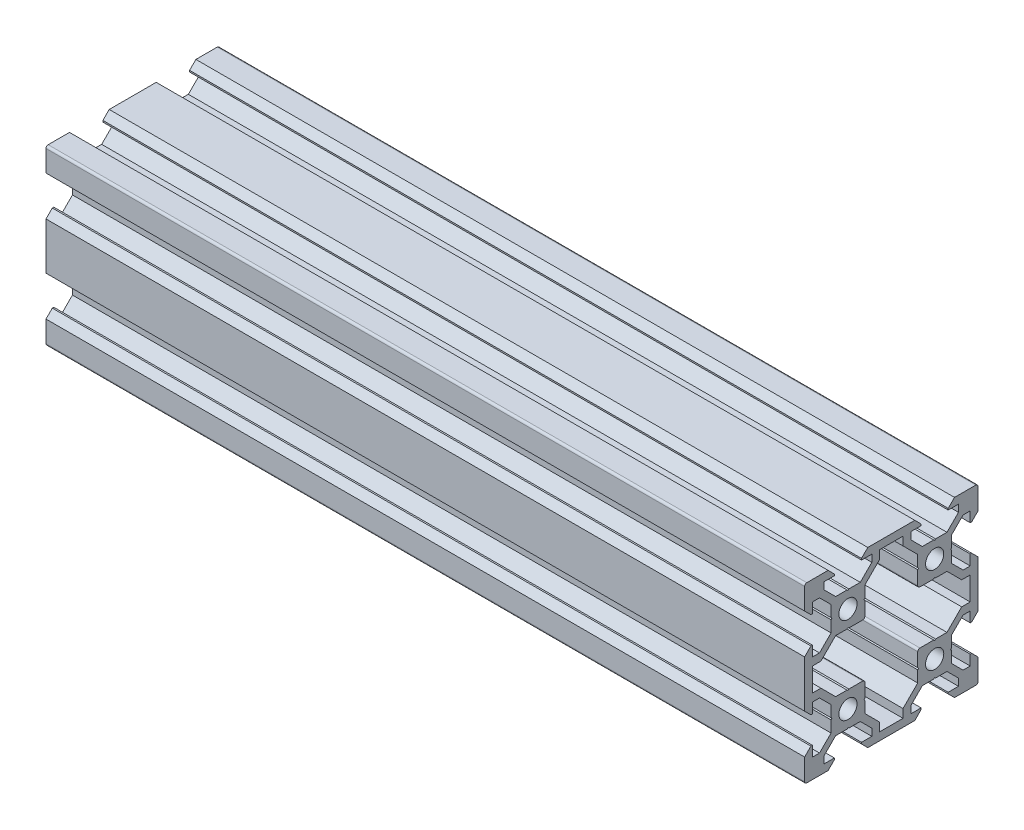
SolidWorks part; units mm, degrees
material "6061-T6 (SS)"
ref_plane "Top" through (0, 0, 0) normal (0, 0, 1) x (1, 0, 0)
ref_plane "Front" through (0, 0, 0) normal (0, 1, 0) x (1, 0, 0)
ref_plane "Right" through (0, 0, 0) normal (1, 0, 0) x (0, 0, -1)
sketch "Profile Sketch" plane through (0, 0, 0) normal (1, 0, 0) x (0, 0, -1)
  line L0 (0, 10) -> (-5.42, 10)
  line L1 (-4.5, 8.2) -> (-4.5, 6.56)
  line L2 (-4.5, 6.56) -> (-7.16, 3.9)
  line L3 (-7.16, 3.9) -> (-9.79, 3.9)
  line L4 (-9.79, 3.9) -> (-10, 3.69)
  line L5 (2.7, 8.2) -> (-2.7, 8.2)
  line L6 (-2.7, 8.2) -> (-2.7, 6.2387)
  line L7 (-2.7, 6.2387) -> (-6.1, 2.8387)
  line L8 (-6.1, 2.8387) -> (-6.1, 0.21)
  line L9 (-6.875, 8.545) -> (-6.875, 8.2)
  line L10 (-6.875, 8.2) -> (-4.5, 8.2)
  line L11 (-6.875, 8.545) -> (-5.42, 10)
  line L12 (0, -10) -> (0, 10) construction
  line L13 (-20, 0) -> (20, 0) construction
  line L14 (-10, -10) -> (-10, 10) construction
  line L21 (-6.6, -3.9) -> (-9.79, -3.9)
  line L25 (-10, 0) -> (-20, 10) construction
  line L26 (-18.545, 3.125) -> (-18.2, 3.125)
  line L31 (-16.2383, -7.3) -> (-12.84, -3.9)
  line L32 (-12.84, -3.9) -> (-10.21, -3.9)
  line L33 (-20, 4.58) -> (-20, 9.5)
  line L34 (-13.9, 2.8387) -> (-13.9, 0.21)
  line L35 (-16.56, 5.5) -> (-13.9, 2.8387)
  line L36 (-12.84, 3.9) -> (-10.21, 3.9)
  line L37 (-15.5, 6.56) -> (-12.84, 3.9)
  line L38 (-15.5, 8.2) -> (-15.5, 6.56)
  line L39 (-13.125, 8.545) -> (-14.58, 10)
  line L40 (-13.125, 8.2) -> (-15.5, 8.2)
  line L41 (-13.125, 8.545) -> (-13.125, 8.2)
  line L42 (-18.2, 3.125) -> (-18.2, 5.5)
  line L43 (-18.545, 3.125) -> (-20, 4.58)
  line L44 (-18.2, 5.5) -> (-16.56, 5.5)
  line L45 (-14.58, 10) -> (-19.5, 10)
  line L46 (-16.56, -5.5) -> (-13.9, -2.8387)
  line L48 (-18.2, -5.5) -> (-16.56, -5.5)
  line L49 (-18.545, -3.125) -> (-20, -4.58)
  line L50 (-18.2, -3.125) -> (-18.2, -5.5)
  line L51 (-20, -4.58) -> (-20, -15.42)
  line L52 (-18.545, -3.125) -> (-18.2, -3.125)
  line L53 (9.79, -3.9) -> (10, -3.69)
  line L99 (-10, 3.69) -> (-10.21, 3.9)
  line L100 (-10, -3.69) -> (-10.21, -3.9)
  line L101 (-9.79, -3.9) -> (-10, -3.69)
  line L102 (-13.9, -0.21) -> (-13.69, 0)
  line L103 (-13.69, 0) -> (-13.9, 0.21)
  line L104 (-13.9, -0.21) -> (-13.9, -2.8387)
  line L105 (-6.1, -0.21) -> (-6.31, 0)
  line L106 (-6.31, 0) -> (-6.1, -0.21)
  line L107 (-6.1, -0.21) -> (-6.1, -3.4)
  line L117 (-16.2383, -7.3) -> (-18.2, -7.3)
  line L118 (20, -10) -> (20, 10) construction
  line L119 (20, -10) -> (-20, -10) construction
  line L120 (-20, -10) -> (-20, 10) construction
  line L121 (20, 10) -> (-20, 10) construction
  line L122 (6.6, -3.9) -> (9.79, -3.9)
  line L123 (10, -3.69) -> (10.21, -3.9)
  line L124 (-18.2, -7.3) -> (-18.2, -12.7)
  line L125 (12.84, -3.9) -> (10.21, -3.9)
  line L126 (-6.31, 0) -> (-6.1, 0.21)
  line L127 (16.2383, -7.3) -> (12.84, -3.9)
  line L128 (20, -4.58) -> (20, -15.42)
  line L129 (18.2, -7.3) -> (18.2, -12.7)
  line L130 (16.2383, -7.3) -> (18.2, -7.3)
  line L131 (18.545, -3.125) -> (18.2, -3.125)
  line L132 (18.2, -3.125) -> (18.2, -5.5)
  line L133 (18.545, -3.125) -> (20, -4.58)
  line L134 (18.2, -5.5) -> (16.56, -5.5)
  line L135 (16.56, -5.5) -> (13.9, -2.8387)
  line L136 (13.9, -0.21) -> (13.9, -2.8387)
  line L137 (13.69, 0) -> (13.9, 0.21)
  line L138 (13.9, -0.21) -> (13.69, 0)
  line L139 (13.9, 2.8387) -> (13.9, 0.21)
  line L140 (18.2, 5.5) -> (16.56, 5.5)
  line L141 (18.545, 3.125) -> (20, 4.58)
  line L142 (18.2, 3.125) -> (18.2, 5.5)
  line L143 (16.56, 5.5) -> (13.9, 2.8387)
  line L144 (18.545, 3.125) -> (18.2, 3.125)
  line L145 (20, 4.58) -> (20, 9.5)
  line L146 (14.58, 10) -> (19.5, 10)
  line L147 (13.125, 8.545) -> (13.125, 8.2)
  line L148 (13.125, 8.2) -> (15.5, 8.2)
  line L149 (13.125, 8.545) -> (14.58, 10)
  line L150 (15.5, 8.2) -> (15.5, 6.56)
  line L151 (15.5, 6.56) -> (12.84, 3.9)
  line L152 (12.84, 3.9) -> (10.21, 3.9)
  line L153 (10, 3.69) -> (10.21, 3.9)
  line L154 (9.79, 3.9) -> (10, 3.69)
  line L155 (6.1, -0.21) -> (6.1, -3.4)
  line L156 (6.1, -0.21) -> (6.31, 0)
  line L157 (6.31, 0) -> (6.1, 0.21)
  line L158 (6.1, 2.8387) -> (6.1, 0.21)
  line L159 (7.16, 3.9) -> (9.79, 3.9)
  line L160 (2.7, 6.2387) -> (6.1, 2.8387)
  line L161 (4.5, 6.56) -> (7.16, 3.9)
  line L162 (6.875, 8.545) -> (6.875, 8.2)
  line L163 (6.875, 8.2) -> (4.5, 8.2)
  line L164 (4.5, 8.2) -> (4.5, 6.56)
  line L165 (2.7, 8.2) -> (2.7, 6.2387)
  line L166 (6.875, 8.545) -> (5.42, 10)
  line L167 (0, 10) -> (5.42, 10)
  line L168 (-20, -24.58) -> (-20, -29.5)
  line L169 (-14.58, -30) -> (-19.5, -30)
  line L170 (-7.16, -23.9) -> (-9.79, -23.9)
  line L171 (-10, -23.69) -> (-10.21, -23.9)
  line L172 (-9.79, -23.9) -> (-10, -23.69)
  line L173 (-12.84, -23.9) -> (-10.21, -23.9)
  line L174 (-13.125, -28.545) -> (-13.125, -28.2)
  line L175 (-13.125, -28.2) -> (-15.5, -28.2)
  line L176 (-13.125, -28.545) -> (-14.58, -30)
  line L177 (-15.5, -28.2) -> (-15.5, -26.56)
  line L178 (-15.5, -26.56) -> (-12.84, -23.9)
  line L179 (-18.2, -25.5) -> (-16.56, -25.5)
  line L180 (-18.545, -23.125) -> (-20, -24.58)
  line L181 (-18.2, -23.125) -> (-18.2, -25.5)
  line L182 (-16.56, -25.5) -> (-13.9, -22.8387)
  line L183 (-18.545, -23.125) -> (-18.2, -23.125)
  line L184 (-13.9, -19.79) -> (-13.9, -17.1613)
  line L185 (-13.69, -20) -> (-13.9, -20.21)
  line L186 (-13.9, -19.79) -> (-13.69, -20)
  line L187 (-13.9, -22.8387) -> (-13.9, -20.21)
  line L188 (-16.2383, -12.7) -> (-18.2, -12.7)
  line L189 (-18.545, -16.875) -> (-18.2, -16.875)
  line L190 (-18.2, -16.875) -> (-18.2, -14.5)
  line L191 (-18.545, -16.875) -> (-20, -15.42)
  line L192 (-18.2, -14.5) -> (-16.56, -14.5)
  line L193 (-16.56, -14.5) -> (-13.9, -17.1613)
  line L194 (-16.2383, -12.7) -> (-12.84, -16.1)
  line L195 (-9.79, -16.1) -> (-10, -16.31)
  line L196 (-10, -16.31) -> (-10.21, -16.1)
  line L197 (-12.84, -16.1) -> (-10.21, -16.1)
  line L198 (-6.6, -16.1) -> (-9.79, -16.1)
  line L199 (-6.1, -19.79) -> (-6.1, -16.6)
  line L200 (-6.1, -22.8387) -> (-6.1, -20.21)
  line L201 (-6.31, -20) -> (-6.1, -20.21)
  line L202 (-6.31, -20) -> (-6.1, -19.79)
  line L203 (-6.1, -19.79) -> (-6.31, -20)
  line L204 (-2.7, -26.2387) -> (-6.1, -22.8387)
  line L205 (-4.5, -26.56) -> (-7.16, -23.9)
  line L206 (-4.5, -28.2) -> (-4.5, -26.56)
  line L207 (-6.875, -28.2) -> (-4.5, -28.2)
  line L208 (-6.875, -28.545) -> (-6.875, -28.2)
  line L209 (-6.875, -28.545) -> (-5.42, -30)
  line L210 (0, -30) -> (-5.42, -30)
  line L211 (0, -30) -> (5.42, -30)
  line L212 (14.58, -30) -> (19.5, -30)
  line L213 (20, -24.58) -> (20, -29.5)
  line L214 (6.875, -28.545) -> (5.42, -30)
  line L215 (2.7, -28.2) -> (2.7, -26.2387)
  line L216 (4.5, -28.2) -> (4.5, -26.56)
  line L217 (6.875, -28.2) -> (4.5, -28.2)
  line L218 (6.875, -28.545) -> (6.875, -28.2)
  line L219 (4.5, -26.56) -> (7.16, -23.9)
  line L220 (2.7, -26.2387) -> (6.1, -22.8387)
  line L221 (7.16, -23.9) -> (9.79, -23.9)
  line L222 (6.1, -22.8387) -> (6.1, -20.21)
  line L223 (9.79, -23.9) -> (10, -23.69)
  line L224 (10, -23.69) -> (10.21, -23.9)
  line L225 (12.84, -23.9) -> (10.21, -23.9)
  line L226 (15.5, -26.56) -> (12.84, -23.9)
  line L227 (15.5, -28.2) -> (15.5, -26.56)
  line L228 (13.125, -28.545) -> (14.58, -30)
  line L229 (13.125, -28.2) -> (15.5, -28.2)
  line L230 (13.125, -28.545) -> (13.125, -28.2)
  line L231 (18.545, -23.125) -> (18.2, -23.125)
  line L232 (16.56, -25.5) -> (13.9, -22.8387)
  line L233 (18.2, -23.125) -> (18.2, -25.5)
  line L234 (18.545, -23.125) -> (20, -24.58)
  line L235 (18.2, -25.5) -> (16.56, -25.5)
  line L236 (13.9, -22.8387) -> (13.9, -20.21)
  line L237 (2.7, -28.2) -> (-2.7, -28.2)
  line L238 (6.31, -20) -> (6.1, -20.21)
  line L239 (6.1, -19.79) -> (6.31, -20)
  line L240 (13.9, -19.79) -> (13.69, -20)
  line L241 (13.69, -20) -> (13.9, -20.21)
  line L242 (6.1, -19.79) -> (6.1, -16.6)
  line L243 (13.9, -19.79) -> (13.9, -17.1613)
  line L244 (16.56, -14.5) -> (13.9, -17.1613)
  line L245 (18.2, -14.5) -> (16.56, -14.5)
  line L246 (18.545, -16.875) -> (20, -15.42)
  line L247 (18.2, -16.875) -> (18.2, -14.5)
  line L248 (18.545, -16.875) -> (18.2, -16.875)
  line L249 (16.2383, -12.7) -> (18.2, -12.7)
  line L250 (16.2383, -12.7) -> (12.84, -16.1)
  line L251 (12.84, -16.1) -> (10.21, -16.1)
  line L252 (10, -16.31) -> (10.21, -16.1)
  line L253 (6.6, -16.1) -> (9.79, -16.1)
  line L254 (9.79, -16.1) -> (10, -16.31)
  line L255 (-2.7, -26.2387) -> (-2.7, -28.2)
  circle A0 centre (-10, 0) radius 2.1
  arc A1 (-19.5, 10) -> (-20, 9.5) centre (-19.5, 9.5) ccw
  arc A2 (-6.6, -3.9) -> (-6.1, -3.4) centre (-6.6, -3.4) ccw
  arc A3 (6.6, -3.9) -> (6.1, -3.4) centre (6.6, -3.4) cw
  circle A4 centre (10, 0) radius 2.1
  arc A5 (19.5, 10) -> (20, 9.5) centre (19.5, 9.5) cw
  arc A6 (-19.5, -30) -> (-20, -29.5) centre (-19.5, -29.5) cw
  arc A7 (-6.6, -16.1) -> (-6.1, -16.6) centre (-6.6, -16.6) cw
  arc A8 (19.5, -30) -> (20, -29.5) centre (19.5, -29.5) ccw
  circle A9 centre (10, -20) radius 2.1
  arc A10 (6.6, -16.1) -> (6.1, -16.6) centre (6.6, -16.6) ccw
  circle A11 centre (-10, -20) radius 2.1
  point P35 (-2.4957, 0)
  point P119 (0, 18.9743)
  point P121 (0, 8.2)
  point P123 (2.4957, 0)
  point P131 (0, 0)
  point P143 (0, 0)
  point P164 (-18.2, -10)
  point P234 (18.2, -10)
  dimension "D4" = 5.42
  dimension "D5" = 40
  dimension "D6" = 4.2
  dimension "D16" = 0.5
  dimension "D17" = 0.5
  dimension "D2" = 45
  dimension "D3" = 20
  dimension "D7" = 1.5
  dimension "D9" = 10
  dimension "D10" = 3.9
  dimension "D11" = 3.9
  dimension "D13" = 3.125
  dimension "D14" = 5.5
  dimension "D15" = 1.64
extrude "Profile Extrude" add sketch "Profile Sketch" along normal blind 175
